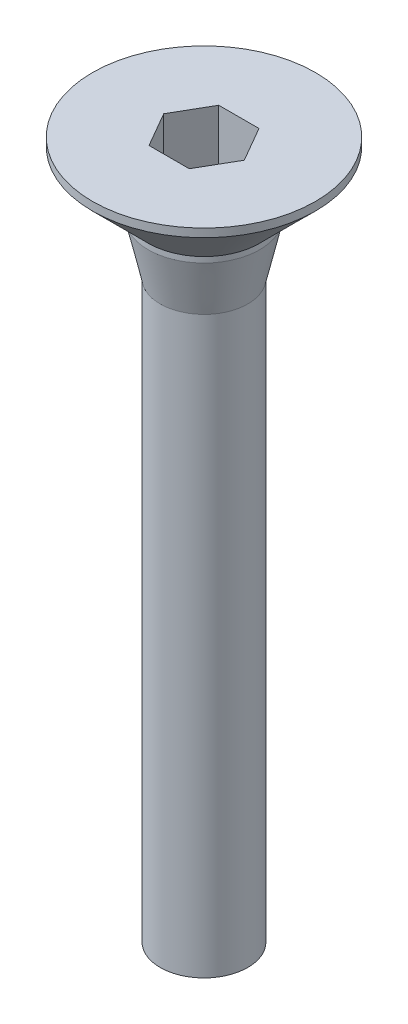
SolidWorks part; units mm, degrees
ref_plane "Vorne" through (0, 0, 0) normal (0, 0, 1) x (1, 0, 0)
ref_plane "Oben" through (0, 0, 0) normal (0, 1, 0) x (1, 0, 0)
ref_plane "Rechts" through (0, 0, 0) normal (1, 0, 0) x (0, 0, -1)
sketch "Skizze1" plane through (0, 0, 0) normal (0, 0, 1) x (1, 0, 0)
  line L0 (0, 0) -> (4, 0)
  line L1 (4, 0) -> (4, -0.3)
  line L2 (4, -0.3) -> (2, -2.3)
  line L3 (2, -2.3) -> (2, -2.5)
  line L4 (2, -2.5) -> (1.5705, -4.4)
  line L5 (1.5705, -4.4) -> (1.5705, -25)
  line L6 (1.5705, -25) -> (0, -25)
  line L7 (0, -25) -> (0, 0)
  line L8 (0, 0) -> (0, -25) construction
  dimension "DK" = 3.141
  dimension "D2" = 45
  dimension "DG" = 4
  dimension "DA" = 8
  dimension "K" = 2.3
  dimension "LS" = 2.5
  dimension "LG" = 4.4
  dimension "L" = 25
revolve "Basis-Rotation" add sketch "Skizze1" angle 360 about L8
sketch "Skizze2" plane through (0, 0, 0) normal (0, 1, 0) x (-1, 0, 0)
  line L0 (1.4434, 0) -> (-1.4434, 0) construction
  line L1 (0, 1.25) -> (0, -1.25) construction
  line L2 (0.7217, -1.25) -> (-0.7217, -1.25)
  line L3 (-0.7217, -1.25) -> (-1.4434, 0)
  line L4 (0.7217, -1.25) -> (1.4434, 0)
  line L5 (0.7217, 1.25) -> (1.4434, 0)
  line L6 (-0.7217, 1.25) -> (-1.4434, 0)
  line L7 (0.7217, 1.25) -> (-0.7217, 1.25)
  dimension "D2" = 120
extrude "Schnitt-Linear austragen1" cut sketch "Skizze2" against normal blind 5.3
